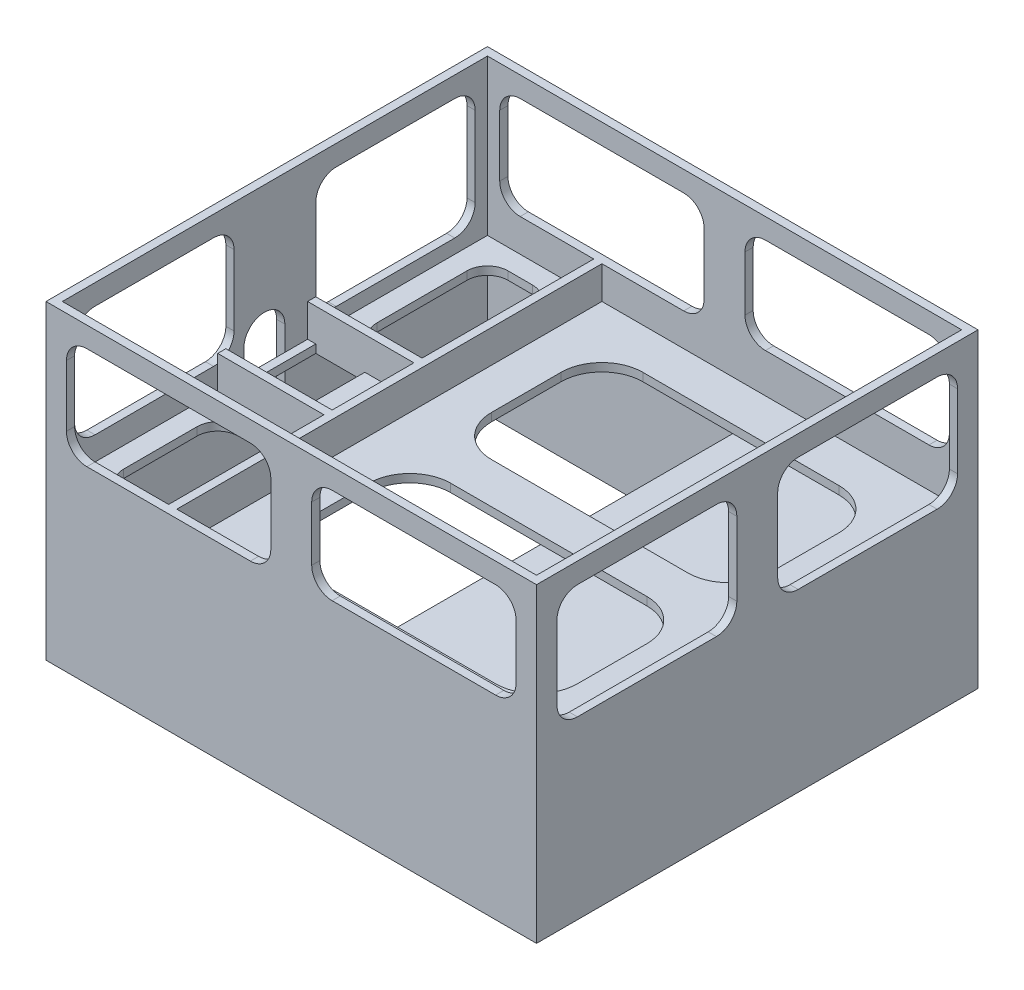
SolidWorks part; units mm, degrees
ref_plane "Front Plane" through (0, 0, 0) normal (0, 0, 1) x (1, 0, 0)
ref_plane "Top Plane" through (0, 0, 0) normal (0, 1, 0) x (1, 0, 0)
ref_plane "Right Plane" through (0, 0, 0) normal (1, 0, 0) x (0, 0, -1)
sketch "Sketch1" plane through (0, 0, 0) normal (0, 1, 0) x (1, 0, 0)
  line L1 (-113.8745, -60.9464) -> (-53.8745, -60.9464)
  line L2 (-113.8745, -60.9464) -> (-113.8745, -6.9464)
  line L3 (-113.8745, -6.9464) -> (-53.8745, -6.9464)
  line L4 (-53.8745, -60.9464) -> (-53.8745, -6.9464)
  dimension "D1" = 60
  dimension "D2" = 54
extrude "Boss-Extrude1" add sketch "Sketch1" along normal blind 38
sketch "Sketch2" plane through (0, 38, 0) normal (0, 1, 0) x (1, 0, 0)
  line L0 (-53.8745, -60.9464) -> (-53.8745, -6.9464) construction
  line L1 (-54.8745, -7.9464) -> (-98.8745, -7.9464)
  line L2 (-54.8745, -7.9464) -> (-54.8745, -59.9464)
  line L3 (-54.8745, -59.9464) -> (-98.8745, -59.9464)
  line L4 (-98.8745, -7.9464) -> (-98.8745, -59.9464)
  line L5 (-53.8745, -6.9464) -> (-113.8745, -6.9464) construction
  line L6 (-113.8745, -60.9464) -> (-53.8745, -60.9464) construction
  dimension "D1" = 1
  dimension "D2" = 1
  dimension "D3" = 1
  dimension "D4" = 44
extrude "Cut-Extrude1" cut sketch "Sketch2" against normal blind 19
sketch "Sketch3" plane through (0, 0, 0) normal (0, -1, 0) x (-1, 0, 0)
  line L0 (113.8745, -60.9464) -> (53.8745, -60.9464) construction
  line L1 (112.8745, -59.9464) -> (77.8745, -59.9464)
  line L2 (112.8745, -59.9464) -> (112.8745, -7.9464)
  line L3 (112.8745, -7.9464) -> (77.8745, -7.9464)
  line L4 (77.8745, -59.9464) -> (77.8745, -7.9464)
  line L5 (113.8745, -6.9464) -> (113.8745, -60.9464) construction
  line L6 (53.8745, -6.9464) -> (113.8745, -6.9464) construction
  dimension "D1" = 1
  dimension "D2" = 35
  dimension "D3" = 1
  dimension "D4" = 1
extrude "Cut-Extrude2" cut sketch "Sketch3" against normal blind 18
sketch "Sketch4" plane through (0, 18, 0) normal (0, -1, 0) x (-1, 0, 0)
  line L0 (77.8745, -59.9464) -> (112.8745, -59.9464) construction
  line L1 (111.8745, -39.9464) -> (105.8745, -39.9464)
  line L2 (111.8745, -39.9464) -> (111.8745, -29.9464)
  line L3 (111.8745, -29.9464) -> (105.8745, -29.9464)
  line L4 (105.8745, -39.9464) -> (105.8745, -29.9464)
  line L5 (112.8745, -7.9464) -> (77.8745, -7.9464) construction
  line L6 (112.8745, -59.9464) -> (112.8745, -7.9464) construction
  dimension "D1" = 20
  dimension "D2" = 22
  dimension "D3" = 1
  dimension "D4" = 6
extrude "Cut-Extrude3" cut sketch "Sketch4" against normal blind 38
sketch "Sketch5" plane through (0, 38, 0) normal (0, 1, 0) x (1, 0, 0)
  line L0 (-53.8745, -6.9464) -> (-113.8745, -6.9464) construction
  line L1 (-98.8745, -59.9464) -> (-112.8745, -59.9464)
  line L2 (-98.8745, -59.9464) -> (-98.8745, -7.9464)
  line L3 (-98.8745, -7.9464) -> (-112.8745, -7.9464)
  line L4 (-112.8745, -59.9464) -> (-112.8745, -7.9464)
  line L5 (-113.8745, -6.9464) -> (-113.8745, -60.9464) construction
  dimension "D1" = 1
  dimension "D2" = 1
extrude "Cut-Extrude5" cut sketch "Sketch5" against normal blind 15
sketch "Sketch6" plane through (0, 23, 0) normal (0, 1, 0) x (1, 0, 0)
  line L0 (-112.8745, -59.9464) -> (-98.8745, -59.9464) construction
  line L1 (-112.8745, -7.9464) -> (-99.8745, -7.9464)
  line L2 (-112.8745, -7.9464) -> (-112.8745, -59.9464)
  line L3 (-112.8745, -59.9464) -> (-99.8745, -59.9464)
  line L4 (-99.8745, -7.9464) -> (-99.8745, -59.9464)
  line L5 (-98.8745, -59.9464) -> (-98.8745, -7.9464) construction
  dimension "D1" = 1
extrude "Cut-Extrude6" cut sketch "Sketch6" against normal blind 4
sketch "Sketch8" plane through (0, 0, 0) normal (0, -1, 0) x (-1, 0, 0)
  line L0 (53.8745, -60.9464) -> (53.8745, -6.9464) construction
  line L1 (73.3745, -11.4464) -> (58.3745, -11.4464)
  line L2 (73.3745, -11.4464) -> (73.3745, -24.4464)
  line L3 (73.3745, -24.4464) -> (58.3745, -24.4464)
  line L4 (58.3745, -11.4464) -> (58.3745, -24.4464)
  line L6 (53.8745, -6.9464) -> (113.8745, -6.9464) construction
  dimension "D1" = 15
  dimension "D2" = 13
  dimension "D3" = 4.5
  dimension "D4" = 4.5
extrude "Cut-Extrude7" cut sketch "Sketch8" against normal blind 6
sketch "Sketch10" plane through (-73.3745, 0, 0) normal (1, 0, 0) x (0, 0, -1)
  line L0 (-11.4464, 6) -> (-11.4464, 0) construction
  line L1 (-24.4464, 6) -> (-11.4464, 6)
  line L2 (-24.4464, 6) -> (-24.4464, 1)
  line L3 (-24.4464, 1) -> (-11.4464, 1)
  line L4 (-11.4464, 6) -> (-11.4464, 1)
  line L5 (-24.4464, 0) -> (-11.4464, 0) construction
  point P7 (-11.9162, 2.727)
  dimension "D1" = 1
extrude "Cut-Extrude8" cut sketch "Sketch10" against normal blind 6
sketch "Sketch11" plane through (0, 0, 0) normal (0, -1, 0) x (1, 0, 0)
  line L0 (-113.8745, 60.9464) -> (-53.8745, 60.9464) construction
  line L1 (-67.8745, 50.9464) -> (-63.8745, 50.9464)
  line L2 (-67.8745, 50.9464) -> (-67.8745, 45.9464)
  line L3 (-67.8745, 45.9464) -> (-63.8745, 45.9464)
  line L4 (-63.8745, 50.9464) -> (-63.8745, 45.9464)
  line L5 (-53.8745, 60.9464) -> (-53.8745, 6.9464) construction
  dimension "D1" = 4
  dimension "D2" = 5
  dimension "D3" = 10
  dimension "D4" = 10
extrude "Cut-Extrude9" cut sketch "Sketch11" against normal blind 3
sketch "Sketch12" plane through (-67.8745, 0, 0) normal (1, 0, 0) x (0, 0, -1)
  line L0 (-50.9464, 3) -> (-50.9464, 0) construction
  line L1 (-45.9464, 3) -> (-50.9464, 3)
  line L2 (-45.9464, 3) -> (-45.9464, 1)
  line L3 (-45.9464, 1) -> (-50.9464, 1)
  line L4 (-50.9464, 3) -> (-50.9464, 1)
  line L5 (-50.9464, 0) -> (-45.9464, 0) construction
  point P7 (-49.533, -3.8829)
  dimension "D1" = 1
extrude "Cut-Extrude10" cut sketch "Sketch12" against normal blind 13
sketch "Sketch13" plane through (-113.8745, 0, 0) normal (-1, 0, 0) x (0, 0, 1)
  line L0 (35.233, 15) -> (35.233, 22) construction
  line L1 (32.733, 15) -> (32.733, 22)
  line L2 (37.733, 15) -> (37.733, 22)
  line L3 (59.9464, 18) -> (7.9464, 18) construction
  line L4 (39.9464, 19) -> (29.9464, 19) construction
  arc A0 (32.733, 15) -> (37.733, 15) centre (35.233, 15) ccw
  arc A1 (37.733, 22) -> (32.733, 22) centre (35.233, 22) ccw
  point P2 (35.233, 18.5)
  point P7 (0, 0)
  point P8 (14.7226, 4.5519)
  dimension "D1" = 3
  dimension "D2" = 3
  dimension "D3" = 2.5
extrude "Cut-Extrude11" cut sketch "Sketch13" against normal blind 1
sketch "Sketch14" plane through (0, 19, 0) normal (0, 1, 0) x (1, 0, 0)
  line L0 (-99.8745, -59.9464) -> (-99.8745, -7.9464) construction
  line L1 (-112.8745, -40.9464) -> (-99.8745, -40.9464)
  line L2 (-112.8745, -40.9464) -> (-112.8745, -39.9464)
  line L3 (-112.8745, -39.9464) -> (-99.8745, -39.9464)
  line L4 (-99.8745, -40.9464) -> (-99.8745, -39.9464)
  line L5 (-112.8745, -37.733) -> (-112.8745, -59.9464) construction
  line L6 (-105.8745, -39.9464) -> (-111.8745, -39.9464) construction
  point P6 (-120.1002, -35.2386)
  point P7 (-123.1182, -45.5085)
  point P8 (-107.1478, -38.8588)
  dimension "D1" = 0
  dimension "D2" = 1
  dimension "D3" = 0
extrude "Boss-Extrude2" add sketch "Sketch14" along normal blind 4
sketch "Sketch15" plane through (0, 19, 0) normal (0, 1, 0) x (1, 0, 0)
  line L0 (-112.8745, -7.9464) -> (-112.8745, -32.733) construction
  line L1 (-112.8745, -29.9464) -> (-99.8745, -29.9464)
  line L2 (-112.8745, -29.9464) -> (-112.8745, -28.9464)
  line L3 (-112.8745, -28.9464) -> (-99.8745, -28.9464)
  line L4 (-99.8745, -29.9464) -> (-99.8745, -28.9464)
  line L5 (-99.8745, -39.9464) -> (-99.8745, -7.9464) construction
  line L6 (-111.8745, -29.9464) -> (-105.8745, -29.9464) construction
  point P8 (-103.7086, -29.8744)
  dimension "D1" = 0
  dimension "D2" = 1
extrude "Boss-Extrude3" add sketch "Sketch15" along normal blind 4
sketch "Sketch16" plane through (0, 19, 0) normal (0, 1, 0) x (1, 0, 0)
  line L0 (-98.8745, -59.9464) -> (-54.8745, -59.9464) construction
  line L1 (-64.8745, -54.9464) -> (-88.8745, -54.9464)
  line L2 (-59.8745, -49.9464) -> (-59.8745, -41.4464)
  line L3 (-64.8745, -36.4464) -> (-88.8745, -36.4464)
  line L4 (-93.8745, -49.9464) -> (-93.8745, -41.4464)
  line L5 (-88.8745, -31.4464) -> (-64.8745, -31.4464)
  line L6 (-93.8745, -26.4464) -> (-93.8745, -17.9464)
  line L7 (-88.8745, -12.9464) -> (-64.8745, -12.9464)
  line L8 (-59.8745, -26.4464) -> (-59.8745, -17.9464)
  line L9 (-54.8745, -59.9464) -> (-54.8745, -7.9464) construction
  line L10 (-98.8745, -7.9464) -> (-98.8745, -59.9464) construction
  line L11 (-54.8745, -7.9464) -> (-98.8745, -7.9464) construction
  arc A0 (-64.8745, -31.4464) -> (-59.8745, -26.4464) centre (-64.8745, -26.4464) ccw
  arc A1 (-64.8745, -12.9464) -> (-59.8745, -17.9464) centre (-64.8745, -17.9464) cw
  arc A2 (-93.8745, -17.9464) -> (-88.8745, -12.9464) centre (-88.8745, -17.9464) cw
  arc A3 (-88.8745, -31.4464) -> (-93.8745, -26.4464) centre (-88.8745, -26.4464) cw
  arc A4 (-88.8745, -54.9464) -> (-93.8745, -49.9464) centre (-88.8745, -49.9464) cw
  arc A5 (-88.8745, -36.4464) -> (-93.8745, -41.4464) centre (-88.8745, -41.4464) ccw
  arc A6 (-59.8745, -41.4464) -> (-64.8745, -36.4464) centre (-64.8745, -41.4464) ccw
  arc A7 (-64.8745, -54.9464) -> (-59.8745, -49.9464) centre (-64.8745, -49.9464) ccw
  point P22 (-93.8745, -12.9464)
  point P25 (-93.8745, -31.4464)
  dimension "D9" = 5
  dimension "D1" = 5
  dimension "D2" = 5
  dimension "D3" = 5
  dimension "D4" = 5
  dimension "D5" = 5
  dimension "D6" = 5
  dimension "D7" = 5
  dimension "D8" = 18.5
extrude "Cut-Extrude12" cut sketch "Sketch16" against normal blind 1
sketch "Sketch17" plane through (0, 19, 0) normal (0, 1, 0) x (1, 0, 0)
  line L0 (-112.8745, -40.9464) -> (-112.8745, -59.9464) construction
  line L1 (-104.8745, -57.4464) -> (-107.8745, -57.4464)
  line L2 (-102.3745, -54.9464) -> (-102.3745, -45.9464)
  line L3 (-104.8745, -43.4464) -> (-107.8745, -43.4464)
  line L4 (-110.3745, -54.9464) -> (-110.3745, -45.9464)
  line L5 (-104.8745, -26.4464) -> (-107.8745, -26.4464)
  line L6 (-102.3745, -23.9464) -> (-102.3745, -12.9464)
  line L7 (-104.8745, -10.4464) -> (-107.8745, -10.4464)
  line L8 (-110.3745, -23.9464) -> (-110.3745, -12.9464)
  line L9 (-99.8745, -59.9464) -> (-99.8745, -40.9464) construction
  line L10 (-112.8745, -40.9464) -> (-99.8745, -40.9464) construction
  line L11 (-112.8745, -59.9464) -> (-99.8745, -59.9464) construction
  line L12 (-99.8745, -28.9464) -> (-112.8745, -28.9464) construction
  line L13 (-112.8745, -7.9464) -> (-112.8745, -28.9464) construction
  line L14 (-99.8745, -28.9464) -> (-99.8745, -7.9464) construction
  line L15 (-99.8745, -7.9464) -> (-112.8745, -7.9464) construction
  arc A0 (-102.3745, -12.9464) -> (-104.8745, -10.4464) centre (-104.8745, -12.9464) ccw
  arc A1 (-107.8745, -10.4464) -> (-110.3745, -12.9464) centre (-107.8745, -12.9464) ccw
  arc A2 (-107.8745, -26.4464) -> (-110.3745, -23.9464) centre (-107.8745, -23.9464) cw
  arc A3 (-104.8745, -26.4464) -> (-102.3745, -23.9464) centre (-104.8745, -23.9464) ccw
  arc A4 (-102.3745, -45.9464) -> (-104.8745, -43.4464) centre (-104.8745, -45.9464) ccw
  arc A5 (-107.8745, -43.4464) -> (-110.3745, -45.9464) centre (-107.8745, -45.9464) ccw
  arc A6 (-107.8745, -57.4464) -> (-110.3745, -54.9464) centre (-107.8745, -54.9464) cw
  arc A7 (-104.8745, -57.4464) -> (-102.3745, -54.9464) centre (-104.8745, -54.9464) ccw
  point P4 (-112.3884, -13.4853)
  dimension "D9" = 2.5
  dimension "D1" = 2.5
  dimension "D2" = 2.5
  dimension "D3" = 2.5
  dimension "D4" = 2.5
  dimension "D5" = 2.5
  dimension "D6" = 2.5
  dimension "D7" = 2.5
  dimension "D8" = 2.5
extrude "Cut-Extrude13" cut sketch "Sketch17" against normal blind 1
sketch "Sketch18" plane through (-53.8745, 0, 0) normal (1, 0, 0) x (0, 0, -1)
  line L0 (-60.9464, 38) -> (-6.9464, 38) construction
  line L1 (-55.9464, 35.5) -> (-38.9464, 35.5)
  line L2 (-58.4464, 33) -> (-58.4464, 24)
  line L3 (-55.9464, 21.5) -> (-38.9464, 21.5)
  line L4 (-36.4464, 33) -> (-36.4464, 24)
  line L5 (-28.9464, 35.5) -> (-11.9464, 35.5)
  line L6 (-31.4464, 33) -> (-31.4464, 24)
  line L7 (-28.9464, 21.5) -> (-11.9464, 21.5)
  line L8 (-9.4464, 33) -> (-9.4464, 24)
  line L9 (-60.9464, 38) -> (-60.9464, 0) construction
  line L10 (-6.9464, 38) -> (-6.9464, 0) construction
  line L11 (-59.9464, 19) -> (-7.9464, 19) construction
  arc A0 (-31.4464, 24) -> (-28.9464, 21.5) centre (-28.9464, 24) ccw
  arc A1 (-11.9464, 21.5) -> (-9.4464, 24) centre (-11.9464, 24) ccw
  arc A2 (-11.9464, 35.5) -> (-9.4464, 33) centre (-11.9464, 33) cw
  arc A3 (-28.9464, 35.5) -> (-31.4464, 33) centre (-28.9464, 33) ccw
  arc A4 (-58.4464, 24) -> (-55.9464, 21.5) centre (-55.9464, 24) ccw
  arc A5 (-38.9464, 21.5) -> (-36.4464, 24) centre (-38.9464, 24) ccw
  arc A6 (-38.9464, 35.5) -> (-36.4464, 33) centre (-38.9464, 33) cw
  arc A7 (-55.9464, 35.5) -> (-58.4464, 33) centre (-55.9464, 33) ccw
  point P26 (-58.4464, 21.5)
  point P29 (-36.4464, 21.5)
  dimension "D9" = 2.5
  dimension "D1" = 2.5
  dimension "D2" = 2.5
  dimension "D3" = 2.5
  dimension "D4" = 2.5
  dimension "D5" = 5
  dimension "D6" = 22
  dimension "D7" = 2.5
  dimension "D8" = 2.5
extrude "Cut-Extrude14" cut sketch "Sketch18" against normal blind 1
sketch "Sketch19" plane through (0, 0, 6.9464) normal (0, 0, -1) x (-1, 0, 0)
  line L0 (53.8745, 38) -> (113.8745, 38) construction
  line L1 (58.8745, 35.5) -> (78.8745, 35.5)
  line L2 (56.3745, 33) -> (56.3745, 26.3041)
  line L3 (58.8745, 23.8041) -> (78.8745, 23.8041)
  line L4 (81.3745, 33) -> (81.3745, 26.3041)
  line L5 (88.8745, 35.5) -> (108.8745, 35.5)
  line L6 (86.3745, 33) -> (86.3745, 25.5)
  line L7 (88.8745, 23) -> (108.8745, 23)
  line L8 (111.3745, 33) -> (111.3745, 25.5)
  line L9 (113.8745, 38) -> (113.8745, 0) construction
  line L10 (53.8745, 38) -> (53.8745, 0) construction
  arc A0 (108.8745, 23) -> (111.3745, 25.5) centre (108.8745, 25.5) ccw
  arc A1 (108.8745, 35.5) -> (111.3745, 33) centre (108.8745, 33) cw
  arc A2 (88.8745, 35.5) -> (86.3745, 33) centre (88.8745, 33) ccw
  arc A3 (86.3745, 25.5) -> (88.8745, 23) centre (88.8745, 25.5) ccw
  arc A4 (78.8745, 23.8041) -> (81.3745, 26.3041) centre (78.8745, 26.3041) ccw
  arc A5 (78.8745, 35.5) -> (81.3745, 33) centre (78.8745, 33) cw
  arc A6 (56.3745, 26.3041) -> (58.8745, 23.8041) centre (58.8745, 26.3041) ccw
  arc A7 (58.8745, 35.5) -> (56.3745, 33) centre (58.8745, 33) ccw
  point P17 (111.3745, 23)
  point P24 (86.3745, 23)
  dimension "D8" = 2.5
  dimension "D1" = 2.5
  dimension "D2" = 2.5
  dimension "D3" = 2.5
  dimension "D4" = 2.5
  dimension "D5" = 5
  dimension "D6" = 25
  dimension "D7" = 0
extrude "Cut-Extrude15" cut sketch "Sketch19" against normal blind 60
sketch "Sketch20" plane through (-113.8745, 0, 0) normal (-1, 0, 0) x (0, 0, 1)
  line L0 (59.9464, 38) -> (7.9464, 38) construction
  line L1 (11.9464, 35.5) -> (26.4464, 35.5)
  line L2 (9.4464, 33) -> (9.4464, 23.222)
  line L3 (11.9464, 20.722) -> (26.4464, 20.722)
  line L4 (28.9464, 33) -> (28.9464, 23.222)
  line L5 (41.4464, 35.5) -> (55.9464, 35.5)
  line L6 (38.9464, 33) -> (38.9464, 24.3756)
  line L7 (41.4464, 21.8756) -> (55.9464, 21.8756)
  line L8 (58.4464, 33) -> (58.4464, 24.3756)
  line L9 (6.9464, 38) -> (6.9464, 0) construction
  line L10 (60.9464, 38) -> (60.9464, 0) construction
  line L11 (6.9464, 38) -> (60.9464, 38) construction
  arc A0 (38.9464, 24.3756) -> (41.4464, 21.8756) centre (41.4464, 24.3756) ccw
  arc A1 (55.9464, 21.8756) -> (58.4464, 24.3756) centre (55.9464, 24.3756) ccw
  arc A2 (55.9464, 35.5) -> (58.4464, 33) centre (55.9464, 33) cw
  arc A3 (41.4464, 35.5) -> (38.9464, 33) centre (41.4464, 33) ccw
  arc A4 (9.4464, 23.222) -> (11.9464, 20.722) centre (11.9464, 23.222) ccw
  arc A5 (26.4464, 20.722) -> (28.9464, 23.222) centre (26.4464, 23.222) ccw
  arc A6 (26.4464, 35.5) -> (28.9464, 33) centre (26.4464, 33) cw
  arc A7 (11.9464, 35.5) -> (9.4464, 33) centre (11.9464, 33) ccw
  point P18 (38.9464, 21.8756)
  point P21 (58.4464, 21.8756)
  dimension "D7" = 2.5
  dimension "D1" = 2.5
  dimension "D2" = 2.5
  dimension "D3" = 10
  dimension "D4" = 2.5
  dimension "D5" = 2.5
  dimension "D6" = 19.5
extrude "Cut-Extrude16" cut sketch "Sketch20" against normal blind 1
